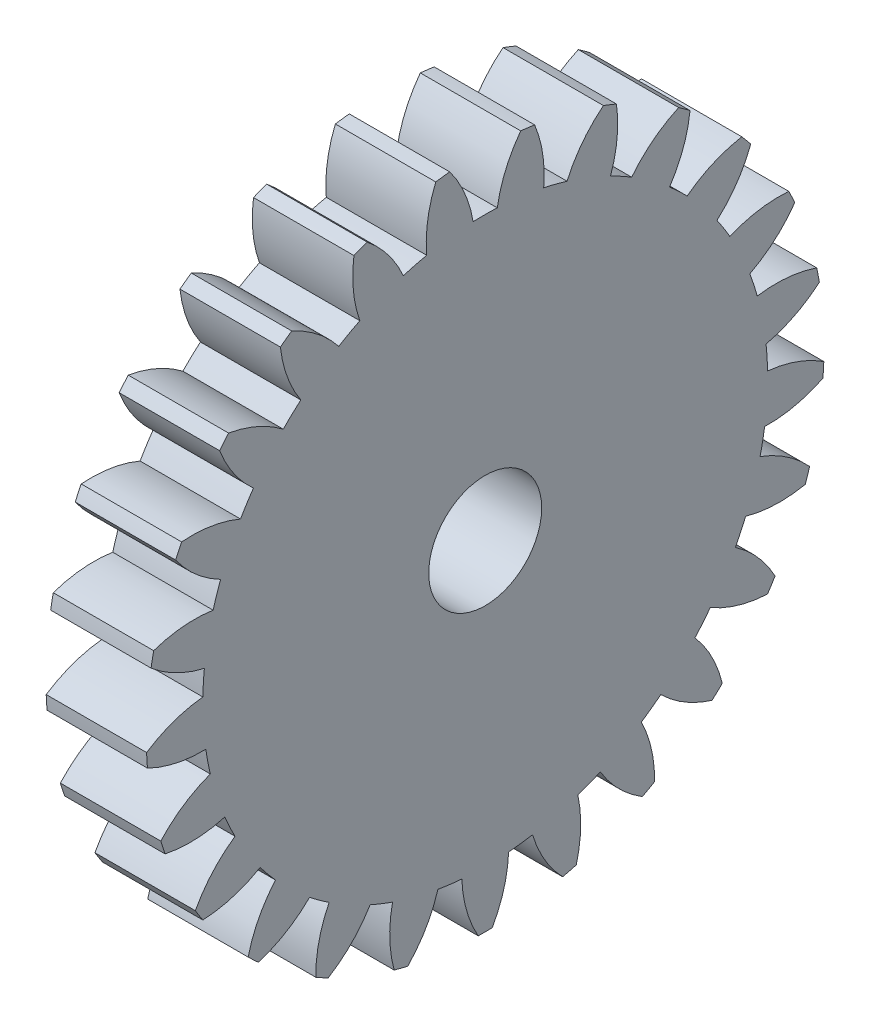
SolidWorks part; units mm, degrees
ref_plane "Plane1" through (0, 0, 0) normal (0, 0, 1) x (1, 0, 0)
ref_plane "Plane2" through (0, 0, 0) normal (0, 1, 0) x (1, 0, 0)
ref_plane "Plane3" through (0, 0, 0) normal (1, 0, 0) x (0, 0, -1)
sketch "HoldingSke" plane through (0, 0, 0) normal (0, 1, 0) x (1, 0, 0)
  line L0 (0, 0) -> (0.9063, -0.4226)
  line L1 (-15, 0) -> (100, 0) construction
  line L2 (0, 0) -> (-2.1039, 2.3779)
  line L3 (0, 0) -> (-11.863, 4.5341)
  line L4 (0, 0) -> (7.8269, 3.6497)
  line L5 (0, 0) -> (-46.8476, -17.4728)
  line L6 (0, 0) -> (-3.3159, -2.2372)
  line L7 (-2.1039, 2.3779) -> (8.6586, 51.2059)
  line L8 (-76.2, 54.61) -> (-76.1, 54.61)
  line L9 (-71.009, 38.7566) -> (-53.1078, 45.2721)
  line L10 (-76.2, 71.12) -> (104.1128, 71.12)
  line L11 (0, 0) -> (-4, 0)
  line L12 (-76.2, 101.6) -> (-76.162, 101.6)
  line L13 (24.9733, 27.94) -> (52.9518, 28.4284)
  line L14 (24.9733, 27.94) -> (24.9743, 27.94)
  line L15 (24.9733, 27.94) -> (100.4006, 29.5858)
  line L16 (-63.627, -1) -> (-12.827, -1)
  circle A0 centre (0, 0) radius 0.4
  circle A1 centre (0, 0) radius 11.249
  circle A2 centre (0, 0) radius 37.5
  circle A3 centre (0, 0) radius 0.4
  dimension "MHD" = 22.498
  dimension "Hub_dia" = 75
  dimension "Bore" = 0.8
  dimension "MBD" = 0.8
  dimension "Num_teeth" = 25
  dimension "Pitch" = 1
  dimension "Overall_len" = 50
  dimension "Show_teeth" = 25
  dimension "Thickness" = 4
  dimension "OAL" = 50.0001
  dimension "T_dim" = 0.1
  dimension "Ap" = 20
  dimension "H" = 19.05
  dimension "Pitch_radius" = 180.3128
  dimension "Width" = 4
  dimension "Backlash" = 0.038
  dimension "Addendum_fac" = 1
  dimension "Dedendum_fac" = 1.25
  dimension "Clearance_fac" = 0.25
  dimension "Dedendum_add" = 0.001
  dimension "Module" = 1
sketch "BasProSke" plane through (0, 0, 0) normal (0, 1, 0) x (1, 0, 0)
  line L0 (-10, 0) -> (60, 0) construction
  line L1 (0, 0) -> (0, 13.5)
  line L2 (0, 0) -> (4, 0)
  line L3 (4, 0) -> (4, 13.5)
  line L4 (4, 13.5) -> (0, 13.5)
  dimension "Thickness" = 4
  dimension "Diameter" = 27
revolve "Base-Revolve" add sketch "BasProSke" angle 360 about L0
sketch "TooCutSke" plane through (0, 0, 0) normal (1, 0, 0) x (0, 0, -1)
  line L1 (0, 0) -> (0, 107) construction
  line L2 (0, 0) -> (-0.8514, 12.471) construction
  line L3 (0, 0) -> (-3.1282, 24.7619) construction
  line L4 (-0.8514, 12.471) -> (-1.5641, 12.3809) construction
  arc A0 (0.4801, 11.2388) -> (-0.4801, 11.2388) centre (0, 0) ccw
  arc A1 (1.4322, 13.4494) -> (-1.4322, 13.4494) centre (0, 0) ccw
  circle A2 centre (0, 0) radius 12.5 construction
  circle A3 centre (0, 0) radius 11.7462 construction
  arc A4 (-0.4801, 11.2388) -> (-1.4322, 13.4494) centre (-5.4133, 10.4244) ccw
  arc A5 (1.4322, 13.4494) -> (0.4801, 11.2388) centre (5.4133, 10.4244) ccw
  dimension "Root_dia" = 22.498
  dimension "Overcut_dia" = 27.0508
  dimension "Pitch_dia" = 25
  dimension "Base_dia" = 23.4923
  dimension "Flank_rad" = 5
  dimension "Half_ang" = 7.2
  dimension "Half_CT" = 0.7184
extrude "ToothCut" cut sketch "TooCutSke" along normal through all
fillet "Breaks" [suppressed] radius 0.02
fillet "RootFillets" [suppressed] radius 0.251
pattern_circular "TeethCuts" count 25 every 14.4 about axis through (-10, 0, 0) along (1, 0, 0) of "ToothCut", "RootFillets", "Breaks"
sketch "HubNeaOneSke" plane through (0, 0, 0) normal (-1, 0, 0) x (0, 0, 1)
  circle A0 centre (0, 0) radius 11.249
  dimension "Diameter" = 22.498
extrude "HubNearOne" [suppressed] add sketch "HubNeaOneSke" along normal blind 46.0001
sketch "HubNeaBotSke" plane through (0, 0, 0) normal (-1, 0, 0) x (0, 0, 1)
  circle A0 centre (0, 0) radius 11.249
  dimension "Diameter" = 22.498
extrude "HubNearBoth" [suppressed] add sketch "HubNeaBotSke" along normal blind 23
ref_plane "FarPln" through (4, 0, 0) normal (1, 0, 0) x (0, 0, -1)
sketch "HubFarSke" plane through (4, 0, 0) normal (1, 0, 0) x (0, 0, -1)
  circle A0 centre (0, 0) radius 11.249
  dimension "Diameter" = 22.498
extrude "HubFar" [suppressed] add sketch "HubFarSke" along normal blind 23
sketch "BorSke" plane through (0, 0, 0) normal (1, 0, 0) x (0, 0, -1)
  circle A0 centre (0, 0) radius 0.4
  dimension "Diameter" = 0.8
extrude "Bore" cut sketch "BorSke" along normal mid plane 100.0001
sketch "KeySke" plane through (0, 0, 0) normal (1, 0, 0) x (0, 0, -1)
  line L0 (-0.05, 0) -> (-0.05, 0.5)
  line L1 (-0.05, 0.5) -> (0.05, 0.5)
  line L2 (0.05, 0.5) -> (0.05, 0)
  line L3 (0, 0) -> (0, 34) construction
  line L4 (-0.05, 0) -> (0.05, 0)
  dimension "Offset" = 0.5
  dimension "Width" = 0.1
extrude "Keyway" [suppressed] cut sketch "KeySke" along normal mid plane 100.0001
pattern_circular "Keyway2" [suppressed] count 2 every 90 about axis through (-10, 0, 0) along (1, 0, 0)
sketch "Sketch1" plane through (4, 0, 0) normal (1, 0, 0) x (0, 0, -1)
  circle A0 centre (0, 0) radius 2.25
  dimension "D1" = 4.5
extrude "Cut-Extrude1" cut sketch "Sketch1" against normal through all
equation "' \"Module@HoldingSke\" = 6.35"
equation "' \"Num_teeth@HoldingSke\" = 12"
equation "' \"Ap@HoldingSke\" =  20"
equation "' \"Ap@HoldingSke\" = 20"
equation "' \"Width@HoldingSke\" = 0.5 * 25.4"
equation "' \"Hub_dia@HoldingSke\"= 1 * 25.4"
equation "' \"Hub_dia@HoldingSke\" = 1 * 25.4"
equation "' \"Overall_len@HoldingSke\" = 1.0 * 25.4"
equation "' \"Bore@HoldingSke\" = 0.75 * 25.4"
equation "' \"T_dim@HoldingSke\" = 0.1 * 25.4"
equation "' \"Width@KeySke\" = 0.25 * 25.4"
equation "' \"Show_teeth@HoldingSke\" = 13"
equation "' \"Backlash@HoldingSke\" = 0.009 * 25.4"
equation "' \"Addendum_fac@HoldingSke\" = 1.0"
equation "' \"Dedendum_fac@HoldingSke\" = 1.25"
equation "' \"Dedendum_add@HoldingSke\" = 0.00005 * 25.4"
equation "' \"Clearance_fac@HoldingSke\" = 0.25"
equation "\"Pitch@HoldingSke\" = 1 / \"Module@HoldingSke\""
equation "\"Overcut_dia@TooCutSke\" = (\"Num_teeth@HoldingSke\" + 2 * \"Addendum_fac@HoldingSke\") / \"Pitch@HoldingSke\" + 0.002 * 25.4"
equation "\"Pitch_dia@TooCutSke\" = \"Num_teeth@HoldingSke\" / \"Pitch@HoldingSke\""
equation "\"Base_dia@TooCutSke\" = \"Num_teeth@HoldingSke\" / \"Pitch@HoldingSke\" * cos((\"Ap@HoldingSke\"  * 3.14159265 / 180))"
equation "\"Root_dia@TooCutSke\" = (\"Num_teeth@HoldingSke\" + 2) / \"Pitch@HoldingSke\" - 2 * (\"Addendum_fac@HoldingSke\" + \"Dedendum_fac@HoldingSke\") / \"Pitch@HoldingSke\" - \"Dedendum_add@HoldingSke\" * 2"
equation "\"Half_ang@TooCutSke\" = 180 / \"Num_teeth@HoldingSke\""
equation "\"Half_CT@TooCutSke\" = \"Num_teeth@HoldingSke\" / \"Pitch@HoldingSke\" * sin((3.14159265 / 2 / \"Num_teeth@HoldingSke\")) / 2 - 7 * \"Backlash@HoldingSke\" / 4"
equation "\"Flank_rad@TooCutSke\" = \"Num_teeth@HoldingSke\" / \"Pitch@HoldingSke\" / 5"
equation "\"Radius@RootFillets\" = \"Clearance_fac@HoldingSke\" / \"Pitch@HoldingSke\" + \"Dedendum_add@HoldingSke\""
equation "\"Break_rad@Breaks\" = 0.02 / \"Pitch@HoldingSke\""
equation "\"Thickness@HoldingSke\" = \"Width@HoldingSke\""
equation "\"OAL@HoldingSke\" = \"Thickness@HoldingSke\""
equation "\"MHD@HoldingSke\" = (\"Num_teeth@HoldingSke\" + 2) / \"Pitch@HoldingSke\" - 2 * (\"Addendum_fac@HoldingSke\" + \"Dedendum_fac@HoldingSke\")  / \"Pitch@HoldingSke\" - \"Dedendum_add@HoldingSke\" * 2"
equation "\"MBD@HoldingSke\" = (\"Num_teeth@HoldingSke\" + 2) / \"Pitch@HoldingSke\" - 2 * (\"Addendum_fac@HoldingSke\" + \"Dedendum_fac@HoldingSke\")  / \"Pitch@HoldingSke\" - \"Dedendum_add@HoldingSke\" * 2 - 0.002 * 25.4"
equation "\"MHD@HoldingSke\" = ((sgn( \"MHD@HoldingSke\" - \"Hub_dia@HoldingSke\" )-1)*( \"MHD@HoldingSke\" - \"Hub_dia@HoldingSke\" ))/-2+ \"Hub_dia@HoldingSke\""
equation "\"MBD@HoldingSke\" = ((sgn( \"MBD@HoldingSke\" - \"Bore@HoldingSke\" )-1)*( \"MBD@HoldingSke\" - \"Bore@HoldingSke\" ))/-2+ \"Bore@HoldingSke\""
equation "\"OAL@HoldingSke\" = ((sgn( \"OAL@HoldingSke\" - \"Overall_len@HoldingSke\" )+1)*( \"OAL@HoldingSke\" - \"Overall_len@HoldingSke\" ))/2 + \"Overall_len@HoldingSke\" + 0.000002 * 25.4"
equation "\"Num_teeth@TeethCuts\" = int( \"Show_teeth@HoldingSke\" ) + 1"
equation "\"Num_teeth@TeethCuts\" = ((sgn( \"Num_teeth@TeethCuts\" - \"Num_teeth@HoldingSke\" )-1)*( \"Num_teeth@TeethCuts\" - \"Num_teeth@HoldingSke\" ))/-2+ \"Num_teeth@HoldingSke\""
equation "\"Num_teeth@TeethCuts\" = ((sgn( \"Num_teeth@TeethCuts\" - 2.0)+1)*( \"Num_teeth@TeethCuts\" - 2.0))/2 +2.0"
equation "\"Angle@TeethCuts\" = 360.0 / \"Num_teeth@HoldingSke\""
equation "\"Diameter@BasProSke\" = (\"Num_teeth@HoldingSke\" + 2 * \"Addendum_fac@HoldingSke\") / \"Pitch@HoldingSke\""
equation "\"Thickness@BasProSke\"  = \"Thickness@HoldingSke\""
equation "' \"Fillet_rad@BasProSke\" =  \"Thickness@HoldingSke\" * 0.05"
equation "' \"Fillet_rad@BasProSke\" = \"Thickness@HoldingSke\" * 0.05"
equation "\"MHD@HoldingSke\" = ((sgn( \"MHD@HoldingSke\" - \"Root_dia@TooCutSke\" )-1)*( \"MHD@HoldingSke\" - \"Root_dia@TooCutSke\" ))/-2+ \"Root_dia@TooCutSke\""
equation "\"Diameter@HubNeaOneSke\" = \"MHD@HoldingSke\""
equation "\"Length@HubNearOne\" = \"OAL@HoldingSke\" - \"Thickness@BasProSke\""
equation "\"Diameter@HubNeaBotSke\" = \"MHD@HoldingSke\""
equation "\"Length@HubNearBoth\" = ( \"OAL@HoldingSke\" - \"Thickness@BasProSke\" ) / 2.0"
equation "\"Thickness@FarPln\" = \"Thickness@BasProSke\""
equation "\"Diameter@HubFarSke\" = \"MHD@HoldingSke\""
equation "\"Length@HubFar\" = ( \"OAL@HoldingSke\" - \"Thickness@BasProSke\" ) / 2.0"
equation "\"Diameter@BorSke\" = \"MBD@HoldingSke\""
equation "\"D1@Bore\" = \"OAL@HoldingSke\" * 2.0"
equation "\"D1@Keyway\" = \"OAL@HoldingSke\" * 2.0"
equation "\"Offset@KeySke\" = \"T_dim@HoldingSke\" + \"MBD@HoldingSke\" / 2.0"
